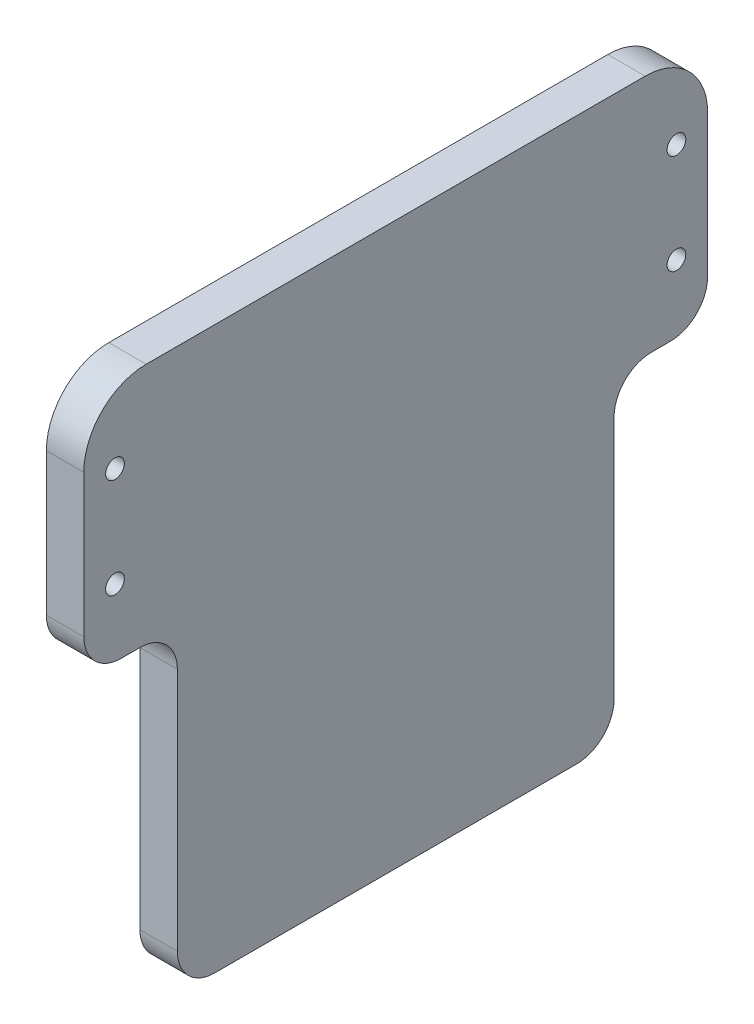
SolidWorks part; units mm, degrees
ref_plane "Front Plane" through (0, 0, 0) normal (0, 0, 1) x (1, 0, 0)
ref_plane "Top Plane" through (0, 0, 0) normal (0, 1, 0) x (1, 0, 0)
ref_plane "Right Plane" through (0, 0, 0) normal (1, 0, 0) x (0, 0, -1)
sketch "Sketch1" plane through (0, 0, 0) normal (1, 0, 0) x (0, 0, -1)
  line L2 (-30, -97.5205) -> (-30, -109.5205)
  line L8 (30, -109.5205) -> (30, -97.5205)
  line L13 (-30, -97.5205) -> (30, -97.5205)
  line L15 (-22, -117.5205) -> (-21.5, -117.5205)
  line L16 (-17.5, -121.5205) -> (-17.5, -139.5205)
  line L18 (22, -117.5205) -> (21.5, -117.5205)
  line L19 (17.5, -121.5205) -> (17.5, -139.5205)
  line L20 (14.5, -142.5205) -> (-14.5, -142.5205)
  arc A0 (22, -117.5205) -> (30, -109.5205) centre (22, -109.5205) ccw
  arc A1 (-22, -117.5205) -> (-30, -109.5205) centre (-22, -109.5205) cw
  arc A2 (17.5, -121.5205) -> (21.5, -117.5205) centre (21.5, -121.5205) cw
  arc A3 (-17.5, -121.5205) -> (-21.5, -117.5205) centre (-21.5, -121.5205) ccw
  arc A4 (14.5, -142.5205) -> (17.5, -139.5205) centre (14.5, -139.5205) ccw
  arc A5 (-14.5, -142.5205) -> (-17.5, -139.5205) centre (-14.5, -139.5205) cw
  point P3 (30, -117.5205)
  point P8 (-30, -117.5205)
  point P13 (17.5, -117.5205)
  point P18 (-17.5, -117.5205)
  point P33 (-17.5, -142.5205)
  dimension "D4" = 3
  dimension "D2" = 8
  dimension "D3" = 4
  dimension "D10" = 12.5
  dimension "D11" = 25
  dimension "D12" = 12.5
extrude "Boss-Extrude1" add sketch "Sketch1" along normal blind 3
sketch "Sketch2" plane through (3, 0, 0) normal (1, 0, 0) x (0, 0, -1)
  line L0 (-22.5, -96.1402) -> (-22.5, -114.2818) construction
  line L1 (-30, -97.5205) -> (-30, -109.5205) construction
  line L2 (22.5, -95.3026) -> (22.5, -118.8726) construction
  line L3 (30, -109.5205) -> (30, -97.5205) construction
  circle A0 centre (-22.5, -103.5205) radius 0.75
  circle A1 centre (-22.5, -111.5205) radius 0.75
  circle A2 centre (22.5, -111.5205) radius 0.75
  circle A3 centre (22.5, -103.5205) radius 0.75
  dimension "D3" = 1.5
  dimension "D4" = 1.5
  dimension "D5" = 1.5
  dimension "D6" = 1.5
  dimension "D1" = 7.5
  dimension "D2" = 7.5
extrude "Cut-Extrude1" cut sketch "Sketch2" against normal through all
sketch "Sketch3" plane through (3, 0, 0) normal (1, 0, 0) x (0, 0, -1)
  line L0 (-30, -97.5205) -> (-25, -97.5205)
  line L1 (30, -97.5205) -> (-30, -97.5205) construction
  line L2 (-25, -97.5205) -> (-25, -113.9367)
  line L3 (-42.8924, -122.4529) -> (-17.5, -122.4529)
  line L4 (-17.5, -121.5205) -> (-17.5, -139.5205) construction
  line L5 (-42.8924, -122.4529) -> (-42.8924, -97.5205)
  line L6 (-42.8924, -97.5205) -> (-30, -97.5205)
  line L7 (0, -84.6879) -> (0, -127.9288) construction
  line L8 (-17.5, -122.4529) -> (-17.5, -119.9367)
  line L9 (-20.5, -116.9367) -> (-22, -116.9367)
  line L10 (20.5, -116.9367) -> (22, -116.9367)
  line L11 (17.5, -122.4529) -> (17.5, -119.9367)
  line L12 (42.8924, -97.5205) -> (30, -97.5205)
  line L13 (42.8924, -122.4529) -> (42.8924, -97.5205)
  line L14 (42.8924, -122.4529) -> (17.5, -122.4529)
  line L15 (25, -97.5205) -> (25, -113.9367)
  line L16 (30, -97.5205) -> (25, -97.5205)
  arc A0 (-30, -109.5205) -> (-22, -117.5205) centre (-22, -109.5205) ccw construction
  arc A1 (-22, -116.9367) -> (-25, -113.9367) centre (-22, -113.9367) cw
  arc A2 (-17.5, -119.9367) -> (-20.5, -116.9367) centre (-20.5, -119.9367) ccw
  arc A3 (17.5, -119.9367) -> (20.5, -116.9367) centre (20.5, -119.9367) cw
  arc A4 (22, -116.9367) -> (25, -113.9367) centre (22, -113.9367) ccw
  point P12 (-25, -116.9367)
  point P34 (25, -116.9367)
  dimension "D2" = 3
  dimension "D3" = 3
  dimension "D1" = 5
extrude "Cut-Extrude2" cut sketch "Sketch3" against normal blind 10
fillet "Fillet1" radius 5 1 edges at (1.5, -97.5205, 25)
fillet "Fillet2" radius 5 1 edges at (1.5, -97.5205, -25)
